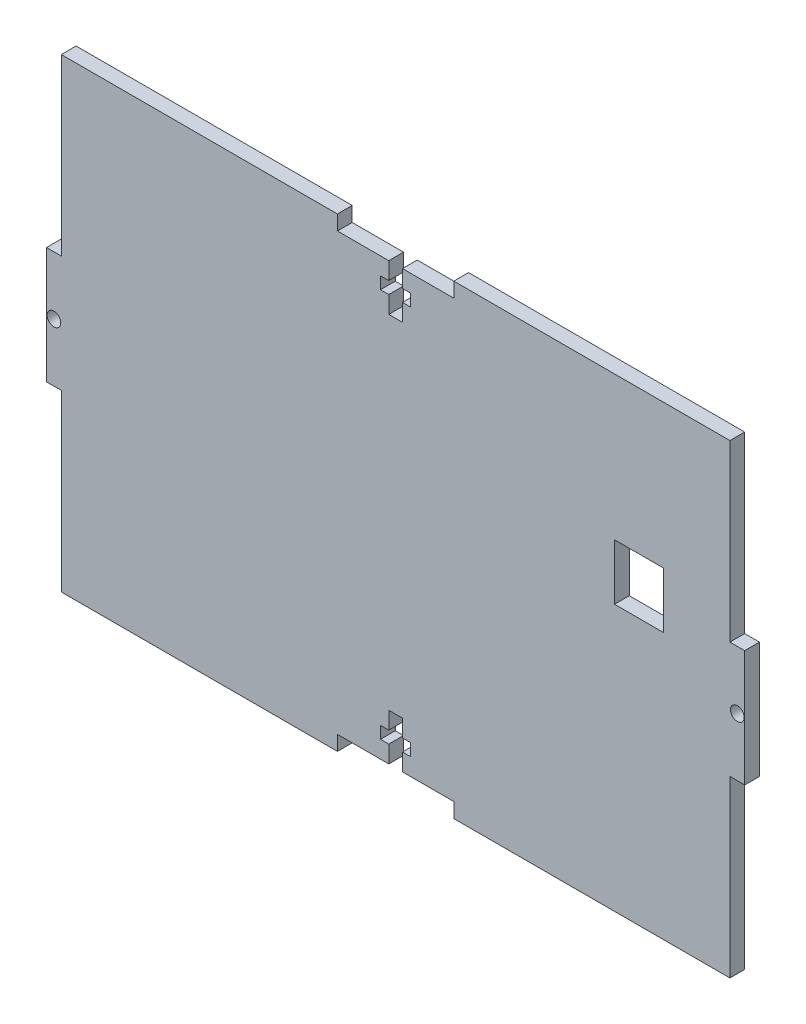
SolidWorks part; units mm, degrees
ref_plane "Front Plane" through (0, 0, 0) normal (0, 0, 1) x (1, 0, 0)
ref_plane "Top Plane" through (0, 0, 0) normal (0, 1, 0) x (1, 0, 0)
ref_plane "Right Plane" through (0, 0, 0) normal (1, 0, 0) x (0, 0, -1)
sketch "Sketch1" plane through (0, 0, 0) normal (0, 0, 1) x (1, 0, 0)
  line L0 (0, 50) -> (0, -50) construction
  line L1 (-71.825, 50) -> (71.825, 50)
  line L2 (-71.825, 50) -> (-71.825, -50)
  line L3 (-71.825, -50) -> (71.825, -50)
  line L4 (71.825, 50) -> (71.825, -50)
  line L5 (-71.825, 50) -> (71.825, -50) construction
  line L6 (-71.825, -50) -> (71.825, 50) construction
  line L7 (-71.825, 0) -> (71.825, 0) construction
  line L8 (-3.25, -40.525) -> (3.25, -40.525)
  line L9 (12.5, 50) -> (-12.5, 50)
  line L10 (12.5, 50) -> (12.5, 46.825)
  line L11 (12.5, 46.825) -> (-12.5, 46.825)
  line L12 (-12.5, 50) -> (-12.5, 46.825)
  line L13 (12.5, 50) -> (-12.5, 46.825) construction
  line L14 (12.5, 46.825) -> (-12.5, 50) construction
  line L15 (-1.47, 46.825) -> (1.47, 46.825)
  line L16 (-1.47, 46.825) -> (-1.47, 36.825)
  line L17 (-1.47, 36.825) -> (1.47, 36.825)
  line L18 (1.47, 46.825) -> (1.47, 36.825)
  line L19 (-1.47, 46.825) -> (1.47, 36.825) construction
  line L20 (-1.47, 36.825) -> (1.47, 46.825) construction
  line L21 (-3.25, 43.125) -> (3.25, 43.125)
  line L22 (-3.25, 43.125) -> (-3.25, 40.525)
  line L23 (-3.25, 40.525) -> (3.25, 40.525)
  line L24 (3.25, 43.125) -> (3.25, 40.525)
  line L25 (-3.25, 43.125) -> (3.25, 40.525) construction
  line L26 (-3.25, 40.525) -> (3.25, 43.125) construction
  line L27 (3.25, -43.125) -> (3.25, -40.525)
  line L28 (-3.25, -43.125) -> (3.25, -43.125)
  line L29 (-3.25, -43.125) -> (-3.25, -40.525)
  line L30 (-1.47, -36.825) -> (1.47, -36.825)
  line L31 (1.47, -46.825) -> (1.47, -36.825)
  line L32 (-1.47, -46.825) -> (1.47, -46.825)
  line L33 (-1.47, -46.825) -> (-1.47, -36.825)
  line L34 (12.5, -46.825) -> (-12.5, -46.825)
  line L35 (-12.5, -50) -> (-12.5, -46.825)
  line L36 (12.5, -50) -> (-12.5, -50)
  line L37 (12.5, -50) -> (12.5, -46.825)
  line L38 (75, -12.5) -> (71.825, -12.5)
  line L39 (-75, 12.5) -> (-71.825, 12.5)
  line L40 (-75, 12.5) -> (-75, -12.5)
  line L41 (-75, -12.5) -> (-71.825, -12.5)
  line L42 (-71.825, 12.5) -> (-71.825, -12.5)
  line L43 (-75, 12.5) -> (-71.825, -12.5) construction
  line L44 (-75, -12.5) -> (-71.825, 12.5) construction
  line L45 (71.825, 12.5) -> (71.825, -12.5)
  line L46 (75, 12.5) -> (71.825, 12.5)
  line L47 (75, 12.5) -> (75, -12.5)
  circle A0 centre (-73.4125, 0) radius 1.47
  circle A1 centre (73.4125, 0) radius 1.47
  point P0 (0, 0)
  point P10 (0, 48.4125)
  point P15 (0, 41.825)
  point P20 (0, 41.825)
  point P37 (-73.4125, 0)
  dimension "D11" = 2.94
  dimension "D1" = 100
  dimension "D2" = 150
  dimension "D3" = 3.175
  dimension "D4" = 10
  dimension "D5" = 2.94
  dimension "D6" = 25
  dimension "D7" = 6.5
  dimension "D8" = 2.6
  dimension "D9" = 6.3
  dimension "D10" = 3.175
extrude "Boss-Extrude1" add sketch "Sketch1" along normal mid plane 3.175 contours L21 L24 L23 L18 L17 L16 L22 L11 L12 L1 L2 L3 L4 L10 | L40 L39 L42 L41 | A0 | L38 L45 L46 L47 | A1
sketch "Sketch3" plane through (0, 0, -1.5875) normal (0, 0, -1) x (-1, 0, 0)
  line L0 (-57.025, 19.1448) -> (-47.525, 19.1448) construction
  line L1 (-47.025, 7.1448) -> (-57.525, 7.1448)
  line L2 (-47.025, 7.1448) -> (-47.025, 19.1448)
  line L3 (-47.025, 19.1448) -> (-57.525, 19.1448)
  line L4 (-57.525, 7.1448) -> (-57.525, 19.1448)
  line L5 (-57.525, 7.6448) -> (-57.525, 18.6448) construction
  line L6 (-47.525, 7.1448) -> (-57.025, 7.1448) construction
  line L7 (-47.025, 18.6448) -> (-47.025, 7.6448) construction
extrude "Cut-Extrude1" cut sketch "Sketch3" against normal through all
